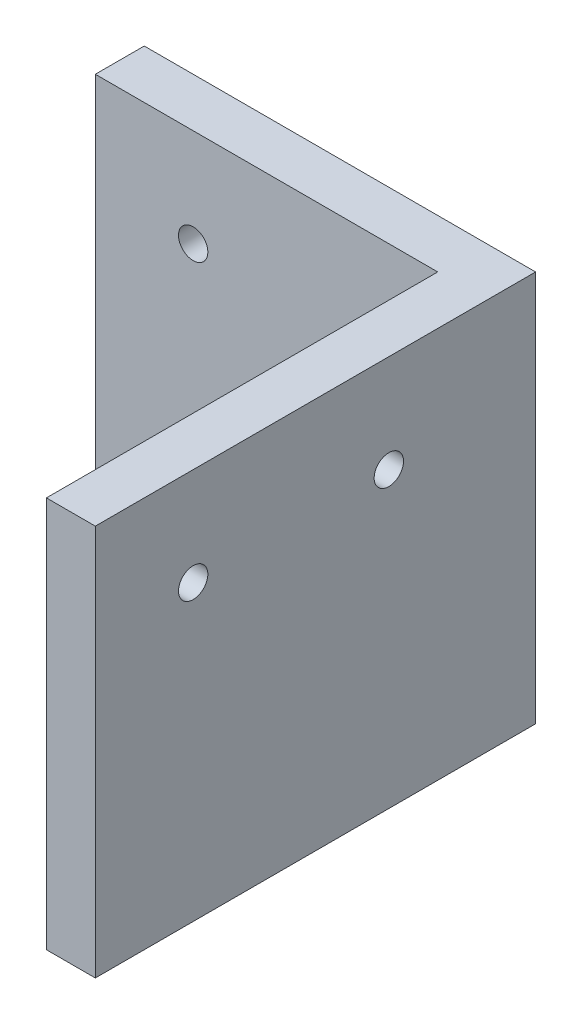
SolidWorks part; units mm, degrees
ref_plane "Front Plane" through (0, 0, 0) normal (0, 0, 1) x (1, 0, 0)
ref_plane "Top Plane" through (0, 0, 0) normal (0, 1, 0) x (1, 0, 0)
ref_plane "Right Plane" through (0, 0, 0) normal (1, 0, 0) x (0, 0, -1)
sketch "Sketch1" plane through (0, 0, 0) normal (0, 0, 1) x (1, 0, 0)
  line L0 (0, 0) -> (0, 95)
  line L1 (0, 95) -> (20, 95)
  line L2 (20, 95) -> (20, 75)
  line L3 (20, 75) -> (40, 75)
  line L4 (40, 75) -> (40, 80)
  line L5 (40, 80) -> (50, 80)
  line L6 (50, 80) -> (50, 75)
  line L7 (50, 75) -> (70, 75)
  line L8 (70, 75) -> (70, 80)
  line L9 (70, 80) -> (80, 80)
  line L10 (80, 80) -> (80, 15)
  line L11 (80, 15) -> (445, 15)
  line L23 (237.9167, 0) -> (0, 0)
  line L24 (262.5, 146.857) -> (262.5, -30.5268)
  line L25 (287.0833, 0) -> (525, 0)
  line L26 (445, 80) -> (445, 15)
  line L27 (455, 80) -> (445, 80)
  line L28 (455, 75) -> (455, 80)
  line L29 (475, 75) -> (455, 75)
  line L30 (485, 80) -> (475, 80)
  line L31 (485, 75) -> (485, 80)
  line L32 (505, 75) -> (485, 75)
  line L33 (505, 95) -> (505, 75)
  line L34 (525, 95) -> (505, 95)
  line L35 (525, 0) -> (525, 95)
  line L36 (475, 75) -> (475, 80)
  line L37 (237.9167, 0) -> (287.0833, 0)
  point P19 (262.5, 15)
  dimension "D1" = 10
  dimension "D2" = 10
  dimension "D3" = 182.5
  dimension "D4" = 20
  dimension "D5" = 20
  dimension "D6" = 20
  dimension "D7" = 20
  dimension "D8" = 5
  dimension "D9" = 5
  dimension "D10" = 65
  dimension "D11" = 80
  dimension "D12" = 95
extrude "Boss-Extrude1" add sketch "Sketch1" along normal blind 597.1 contours L23 L37 L24 L11 L10 L9 L8 L7 L6 L5 L4 L3 L2 L1 L0 | L24 L37 L25 L35 L34 L33 L32 L31 L30 L36 L29 L28 L27 L26 L11
sketch "Sketch2" plane through (0, 15, 0) normal (0, 1, 0) x (1, 0, 0)
  line L0 (80, 0) -> (445, 0) construction
  line L1 (187.3, 0) -> (252.5, 0)
  line L2 (187.3, 0) -> (187.3, -400)
  line L3 (187.3, -400) -> (252.5, -400)
  line L4 (252.5, 0) -> (252.5, -400)
  line L5 (80, -597.1) -> (445, -597.1) construction
  line L6 (272.5, -597.1) -> (337.7, -597.1)
  line L7 (272.5, -597.1) -> (272.5, -197.1)
  line L8 (272.5, -197.1) -> (337.7, -197.1)
  line L9 (337.7, -597.1) -> (337.7, -197.1)
  line L10 (445, -597.1) -> (445, 0) construction
  dimension "D1" = 400
  dimension "D2" = 400
  dimension "D3" = 65.2
  dimension "D4" = 65.2
  dimension "D5" = 20
  dimension "D6" = 107.3
extrude "Cut-Extrude1" cut sketch "Sketch2" against normal through all
sketch "Sketch3" plane through (0, 15, 0) normal (0, 1, 0) x (1, 0, 0)
  line L1 (80, 0) -> (445, 0)
  line L2 (80, 0) -> (80, -597.1)
  line L3 (80, -597.1) -> (445, -597.1)
  line L4 (445, 0) -> (445, -597.1)
  line L5 (187.3, 0) -> (252.5, 0)
  line L6 (187.3, 0) -> (187.3, -400)
  line L7 (187.3, -400) -> (252.5, -400)
  line L8 (252.5, 0) -> (252.5, -400)
  line L9 (272.5, -197.1) -> (337.7, -197.1)
  line L10 (272.5, -197.1) -> (272.5, -597.1)
  line L11 (272.5, -597.1) -> (337.7, -597.1)
  line L12 (337.7, -197.1) -> (337.7, -597.1)
  line M1 (187.3, -400) -> (187.3, 0)
  line M2 (187.3, 0) -> (80, 0)
  line M3 (80, 0) -> (80, -597.1)
  line M4 (80, -597.1) -> (272.5, -597.1)
  line M5 (272.5, -597.1) -> (272.5, -197.1)
  line M6 (272.5, -197.1) -> (337.7, -197.1)
  line M7 (337.7, -197.1) -> (337.7, -597.1)
  line M8 (337.7, -597.1) -> (445, -597.1)
  line M9 (445, -597.1) -> (445, 0)
  line M10 (445, 0) -> (252.5, 0)
  line M11 (252.5, 0) -> (252.5, -400)
  line M12 (252.5, -400) -> (187.3, -400)
extrude "Boss-Extrude2" add sketch "Sketch3" along normal blind 8 contours M12 M1 M2 M3 M4 M5 M6 M7 M8 M9 M10 M11
sketch "Sketch4" plane through (0, 0, 0) normal (0, -1, 0) x (1, 0, 0)
  line L1 (0, 597.1) -> (525, 597.1)
  line L2 (0, 597.1) -> (0, 0)
  line L3 (0, 0) -> (525, 0)
  line L4 (525, 597.1) -> (525, 0)
extrude "Boss-Extrude3" add sketch "Sketch4" along normal blind 7
sketch "Sketch5" plane through (0, 23, 0) normal (0, 1, 0) x (1, 0, 0)
  line L1 (80, 0) -> (445, 0)
  line L2 (80, 0) -> (80, -597.1)
  line L3 (80, -597.1) -> (445, -597.1)
  line L4 (445, 0) -> (445, -597.1)
extrude "Cut-Extrude2" cut sketch "Sketch5" against normal blind 10
sketch "Sketch6" plane through (525, 0, 0) normal (1, 0, 0) x (0, 0, -1)
  line L0 (-597.1, 95) -> (0, 95) construction
  line L1 (-324.55, 95) -> (-272.55, 95)
  line L2 (-324.55, 95) -> (-324.55, 55)
  line L3 (-324.55, 55) -> (-272.55, 55)
  line L4 (-272.55, 95) -> (-272.55, 55)
  line L6 (-597.1, -7) -> (-597.1, 95) construction
  circle A0 centre (-318.55, 79) radius 2.125
  circle A1 centre (-278.55, 79) radius 2.125
  circle A2 centre (-278.55, 63) radius 2.125
  circle A3 centre (-318.55, 63) radius 2.125
  circle A4 centre (-318.55, 79) radius 2.125
  circle A5 centre (-278.55, 79) radius 2.125
  circle A6 centre (-278.55, 63) radius 2.125
  circle A7 centre (-318.55, 63) radius 2.125
  dimension "D4" = 4.25
  dimension "D1" = 52
  dimension "D2" = 40
  dimension "D3" = 272.55
  dimension "D5" = 40
  dimension "D6" = 40
  dimension "D7" = 16
  dimension "D8" = 16
  dimension "D9" = 6
  dimension "D10" = 8
extrude "Cut-Extrude3" cut sketch "Sketch6" against normal up to next contours A0 | A3 | A2 | A1
cosmetic thread "Cosmetic Thread5" parameters "D2"=5.5
cosmetic thread "Cosmetic Thread6" parameters "D2"=5.5
cosmetic thread "Cosmetic Thread7" parameters "D2"=5.5
cosmetic thread "Cosmetic Thread8" parameters "D2"=5.5
sketch "Sketch7" plane through (0, 75, 0) normal (0, 1, 0) x (1, 0, 0)
  line L1 (485, 0) -> (505, 0)
  line L2 (485, 0) -> (485, -597.1)
  line L3 (485, -597.1) -> (505, -597.1)
  line L4 (505, 0) -> (505, -597.1)
extrude "Cut-Extrude4" cut sketch "Sketch7" against normal blind 5
sketch "Sketch8" plane through (445, 0, 0) normal (-1, 0, 0) x (0, 0, 1)
  line L0 (597.1, 80) -> (0, 80) construction
  line L1 (269.8676, 50) -> (324.923, 50)
  line L2 (269.8676, 50) -> (269.8676, 70)
  line L3 (269.8676, 70) -> (324.923, 70)
  line L4 (324.923, 50) -> (324.923, 70)
  dimension "D1" = 20
  dimension "D2" = 55.0555
  dimension "D3" = 10
extrude "Cut-Extrude6" cut sketch "Sketch8" against normal blind 60
sketch "Sketch13" plane through (0, 50, 0) normal (0, 1, 0) x (1, 0, 0)
  line L0 (445, -269.8676) -> (445, -324.923) construction
  line L1 (445, -290.3007) -> (485, -290.3007)
  line L2 (445, -290.3007) -> (445, -305.3007)
  line L3 (445, -305.3007) -> (485, -305.3007)
  line L4 (485, -290.3007) -> (485, -305.3007)
  dimension "D1" = 15
  dimension "D2" = 40
extrude "Boss-Extrude4" add sketch "Sketch13" along normal up to next
sketch "Sketch14" plane through (0, 75, 0) normal (0, 1, 0) x (1, 0, 0)
  line L1 (20, 0) -> (40, 0)
  line L2 (20, 0) -> (20, -597.1)
  line L3 (20, -597.1) -> (40, -597.1)
  line L4 (40, 0) -> (40, -597.1)
extrude "Cut-Extrude7" cut sketch "Sketch14" against normal blind 5
sketch "Sketch15" plane through (0, 0, 0) normal (-1, 0, 0) x (0, 0, 1)
  line L0 (597.1, 95) -> (0, 95) construction
  line L1 (10, 95) -> (37, 95)
  line L2 (10, 95) -> (10, 49.6)
  line L3 (10, 49.6) -> (37, 49.6)
  line L4 (37, 95) -> (37, 49.6)
  line L5 (0, -7) -> (0, 95) construction
  line L10 (298.55, -7) -> (298.55, 95)
  line L11 (597.1, -7) -> (0, -7) construction
  line L12 (587.1, 49.6) -> (560.1, 49.6)
  line L13 (587.1, 95) -> (560.1, 95)
  line L14 (587.1, 95) -> (587.1, 49.6)
  line L15 (560.1, 95) -> (560.1, 49.6)
  circle A0 centre (13.5, 82.3) radius 1.33
  circle A1 centre (33.5, 82.3) radius 1.33
  circle A2 centre (33.5, 62.3) radius 1.33
  circle A3 centre (13.5, 62.3) radius 1.33
  circle A4 centre (563.6, 62.3) radius 1.33
  circle A5 centre (563.6, 82.3) radius 1.33
  circle A6 centre (583.6, 82.3) radius 1.33
  circle A7 centre (583.6, 62.3) radius 1.33
  circle A8 centre (13.5, 82.3) radius 1.33
  circle A9 centre (33.5, 82.3) radius 1.33
  circle A10 centre (33.5, 62.3) radius 1.33
  circle A11 centre (13.5, 62.3) radius 1.33
  dimension "D2" = 2.66
  dimension "D1" = 10
  dimension "D3" = 45.4
  dimension "D4" = 27
  dimension "D5" = 20
  dimension "D6" = 20
  dimension "D7" = 20
  dimension "D8" = 20
  dimension "D9" = 3.5
  dimension "D10" = 12.7
extrude "Cut-Extrude8" cut sketch "Sketch15" against normal up to next contours A0 | A1 | A3 | A2 | A5 | A7 | A4 | A6
cosmetic thread "Cosmetic Thread9" parameters "D2"=3.2
cosmetic thread "Cosmetic Thread10" parameters "D2"=3.2
cosmetic thread "Cosmetic Thread11" parameters "D2"=3.2
cosmetic thread "Cosmetic Thread12" parameters "D2"=3.2
cosmetic thread "Cosmetic Thread13" parameters "D2"=3.2
cosmetic thread "Cosmetic Thread14" parameters "D2"=3.2
cosmetic thread "Cosmetic Thread15" parameters "D2"=3.2
cosmetic thread "Cosmetic Thread16" parameters "D2"=3.2
sketch "Sketch16" plane through (80, 0, 0) normal (1, 0, 0) x (0, 0, -1)
  line L0 (-597.1, 80) -> (-597.1, 13) construction
  line L1 (-592.1, 70) -> (-557.1, 70)
  line L2 (-592.1, 70) -> (-592.1, 55)
  line L3 (-592.1, 55) -> (-557.1, 55)
  line L4 (-557.1, 70) -> (-557.1, 55)
  line L5 (-597.1, 80) -> (0, 80) construction
  line L6 (0, 80) -> (0, 13) construction
  line L7 (-40, 55) -> (-5, 55)
  line L8 (-40, 55) -> (-40, 70)
  line L9 (-40, 70) -> (-5, 70)
  line L10 (-5, 55) -> (-5, 70)
  dimension "D1" = 5
  dimension "D2" = 15
  dimension "D3" = 10
  dimension "D4" = 35
  dimension "D5" = 10
  dimension "D6" = 5
  dimension "D7" = 35
  dimension "D8" = 15
extrude "Cut-Extrude9" cut sketch "Sketch16" against normal blind 60
sketch "Sketch17" plane through (0, -7, 0) normal (0, -1, 0) x (1, 0, 0)
  line L0 (525, 0) -> (525, 597.1) construction
  line L1 (465, 373.55) -> (525, 373.55)
  line L2 (465, 373.55) -> (465, 223.55)
  line L3 (465, 223.55) -> (525, 223.55)
  line L4 (525, 373.55) -> (525, 223.55)
  line L5 (525, 597.1) -> (0, 597.1) construction
  dimension "D1" = 150
  dimension "D2" = 223.55
  dimension "D3" = 60
extrude "Cut-Extrude10" cut sketch "Sketch17" against normal blind 40
sketch "Sketch18" plane through (0, 13, 0) normal (0, 1, 0) x (1, 0, 0)
  line L1 (427, -286.05) -> (415, -286.05)
  line L2 (427, -286.05) -> (427, -302.05)
  line L3 (427, -302.05) -> (415, -302.05)
  line L4 (415, -286.05) -> (415, -302.05)
  line L5 (417, -286.05) -> (425, -286.05)
  line L6 (445, 0) -> (252.5, 0) construction
  line L7 (417, -286.05) -> (417, -279.05)
  line L8 (445, -597.1) -> (445, 0) construction
  line L9 (417, -279.05) -> (425, -279.05)
  line L10 (425, -286.05) -> (425, -279.05)
  line L11 (417, -302.05) -> (425, -302.05)
  line L12 (417, -302.05) -> (417, -309.05)
  line L13 (417, -309.05) -> (425, -309.05)
  line L14 (425, -302.05) -> (425, -309.05)
  dimension "D1" = 12
  dimension "D2" = 16
  dimension "D3" = 286.05
  dimension "D4" = 30
  dimension "D5" = 8
  dimension "D6" = 7
  dimension "D7" = 2
  dimension "D8" = 8
  dimension "D9" = 7
  dimension "D10" = 2
extrude "Cut-Extrude11" cut sketch "Sketch18" against normal through all contours L1 L4 L3 L2
sketch "Sketch19" plane through (0, 13, 0) normal (0, 1, 0) x (1, 0, 0)
  line L0 (427, -286.05) -> (415, -286.05) construction
  line L1 (417, -286.05) -> (425, -286.05)
  line L2 (417, -286.05) -> (417, -279.05)
  line L3 (417, -279.05) -> (425, -279.05)
  line L4 (425, -286.05) -> (425, -279.05)
  line L5 (427, -302.05) -> (415, -302.05) construction
  line L6 (417, -302.05) -> (425, -302.05)
  line L7 (417, -302.05) -> (417, -309.05)
  line L8 (417, -309.05) -> (425, -309.05)
  line L9 (425, -302.05) -> (425, -309.05)
  line L10 (415, -286.05) -> (415, -302.05) construction
  dimension "D1" = 8
  dimension "D2" = 8
  dimension "D3" = 7
  dimension "D4" = 7
  dimension "D5" = 2
  dimension "D6" = 2
extrude "Cut-Extrude12" cut sketch "Sketch19" against normal blind 10
sketch "Sketch20" plane through (525, 0, 0) normal (1, 0, 0) x (0, 0, -1)
  circle A0 centre (-318.55, 79) radius 2.7599
  circle A1 centre (-318.55, 63) radius 2.758
  circle A2 centre (-278.55, 63) radius 2.7761
  circle A3 centre (-278.55, 79) radius 2.7514
extrude "Cut-Extrude13" cut sketch "Sketch20" against normal up to next
sketch "Sketch21" plane through (0, 0, 0) normal (-1, 0, 0) x (0, 0, 1)
  circle A0 centre (13.5, 82.3) radius 1.6434
  circle A1 centre (13.5, 62.3) radius 1.6389
  circle A2 centre (33.5, 62.3) radius 1.6445
  circle A3 centre (33.5, 82.3) radius 1.706
  circle A4 centre (563.6, 62.3) radius 1.6454
  circle A5 centre (583.6, 62.3) radius 1.6466
  circle A6 centre (583.6, 82.3) radius 1.6613
  circle A7 centre (563.6, 82.3) radius 1.7012
extrude "Cut-Extrude14" cut sketch "Sketch21" against normal up to next
sketch "Sketch22" plane through (445, 0, 0) normal (-1, 0, 0) x (0, 0, 1)
  line L1 (290.3007, 70) -> (305.3007, 70)
  line L2 (290.3007, 70) -> (290.3007, 50)
  line L3 (290.3007, 50) -> (305.3007, 50)
  line L4 (305.3007, 70) -> (305.3007, 50)
extrude "Cut-Extrude15" cut sketch "Sketch22" against normal up to next
sketch "Sketch24" plane through (525, 0, 0) normal (1, 0, 0) x (0, 0, -1)
  line L0 (-597.1, -7) -> (-597.1, 95) construction
  line L1 (-597.1, 95) -> (0, 95) construction
  line L4 (0, -7) -> (0, 95) construction
  circle A0 centre (-583.6, 82.3) radius 1.5
  circle A1 centre (-563.6, 82.3) radius 1.5
  circle A2 centre (-583.6, 62.3) radius 1.5
  circle A3 centre (-563.6, 62.3) radius 1.5
  circle A4 centre (-33.5, 82.3) radius 1.5
  circle A5 centre (-13.5, 82.3) radius 1.5
  circle A6 centre (-13.5, 62.3) radius 1.5
  circle A7 centre (-33.5, 62.3) radius 1.5
  dimension "D1" = 3
  dimension "D2" = 13.5
  dimension "D3" = 12.7
  dimension "D4" = 20
  dimension "D5" = 13.5
  dimension "D6" = 12.7
  dimension "D7" = 20
  dimension "D8" = 20
  dimension "D9" = 20
  dimension "D10" = 13.5
  dimension "D11" = 20
  dimension "D12" = 20
  dimension "D13" = 20
  dimension "D14" = 20
  dimension "D15" = 12.7
  dimension "D16" = 13.5
  dimension "D17" = 12.7
extrude "Cut-Extrude16" cut sketch "Sketch24" against normal up to next
sketch "Sketch27" plane through (445, 0, 0) normal (-1, 0, 0) x (0, 0, 1)
  line L0 (597.1, 80) -> (0, 80) construction
  line L1 (592.1, 70) -> (557.1, 70)
  line L2 (592.1, 70) -> (592.1, 55)
  line L3 (592.1, 55) -> (557.1, 55)
  line L4 (557.1, 70) -> (557.1, 55)
  line L5 (597.1, 80) -> (597.1, 13) construction
  dimension "D1" = 10
  dimension "D2" = 5
  dimension "D3" = 35
  dimension "D4" = 15
extrude "Cut-Extrude17" cut sketch "Sketch27" against normal blind 60
sketch "Sketch28" plane through (445, 0, 0) normal (-1, 0, 0) x (0, 0, 1)
  line L1 (0, 80) -> (40, 80)
  line L2 (0, 80) -> (0, 55)
  line L3 (0, 55) -> (40, 55)
  line L4 (40, 80) -> (40, 55)
  line L5 (40, 55) -> (5, 55)
  line L6 (40, 55) -> (40, 70)
  line L7 (40, 70) -> (5, 70)
  line L8 (5, 55) -> (5, 70)
  circle M9 centre (13.5, 62.3) radius 1.5
  circle M10 centre (33.5, 62.3) radius 1.5
  dimension "D1" = 40
  dimension "D2" = 25
  dimension "D3" = 15
  dimension "D4" = 35
extrude "Cut-Extrude18" cut sketch "Sketch28" against normal blind 60 contours L8 L3 L4 L7 M10 M9
sketch "Sketch29" plane through (0, -7, 0) normal (0, -1, 0) x (1, 0, 0)
  line L0 (0, 597.1) -> (0, 0) construction
  line L1 (0, 373.55) -> (60, 373.55)
  line L2 (0, 373.55) -> (0, 223.55)
  line L3 (0, 223.55) -> (60, 223.55)
  line L4 (60, 373.55) -> (60, 223.55)
  dimension "D1" = 60
  dimension "D2" = 150
extrude "Cut-Extrude19" cut sketch "Sketch29" against normal blind 40
sketch "Sketch33" plane through (0, 0, 0) normal (-1, 0, 0) x (0, 0, 1)
  line L0 (597.1, 95) -> (0, 95) construction
  line L1 (597.1, -7) -> (597.1, 95) construction
  circle A0 centre (318.55, 79) radius 2.5
  circle A1 centre (319.3565, 63) radius 2.5
  circle A2 centre (278.55, 79) radius 2.5
  circle A3 centre (279.3565, 63) radius 2.5
  dimension "D1" = 5
  dimension "D2" = 40
  dimension "D3" = 16
  dimension "D4" = 40
  dimension "D5" = 16
  dimension "D6" = 16
  dimension "D7" = 278.55
extrude "Cut-Extrude20" cut sketch "Sketch33" against normal up to next
sketch "Sketch37" plane through (80, 0, 0) normal (1, 0, 0) x (0, 0, -1)
  line L0 (-597.1, 80) -> (0, 80) construction
  line L1 (-327.18, 50) -> (-272.18, 50)
  line L2 (-327.18, 50) -> (-327.18, 70)
  line L3 (-327.18, 70) -> (-272.18, 70)
  line L4 (-272.18, 50) -> (-272.18, 70)
  line L5 (0, 80) -> (0, 13) construction
  dimension "D1" = 20
  dimension "D2" = 55
  dimension "D3" = 10
  dimension "D4" = 272.18
extrude "Cut-Extrude21" cut sketch "Sketch37" against normal blind 60
sketch "Sketch39" plane through (0, 0, 0) normal (-1, 0, 0) x (0, 0, 1)
  line L0 (597.1, 95) -> (0, 95) construction
  line L1 (3, 95) -> (8, 95)
  line L2 (3, 95) -> (3, 55)
  line L3 (3, 55) -> (8, 55)
  line L4 (8, 95) -> (8, 55)
  line L5 (0, -7) -> (0, 95) construction
  line L6 (597.1, -7) -> (597.1, 95) construction
  line L7 (589.1, 95) -> (594.1, 95)
  line L8 (589.1, 95) -> (589.1, 55)
  line L9 (589.1, 55) -> (594.1, 55)
  line L10 (594.1, 95) -> (594.1, 55)
  dimension "D1" = 3
  dimension "D2" = 5
  dimension "D3" = 40
  dimension "D4" = 3
  dimension "D5" = 5
  dimension "D6" = 40
extrude "Boss-Extrude6" add sketch "Sketch39" along normal blind 40
sketch "Sketch41" plane through (0, 0, 3) normal (0, 0, -1) x (-1, 0, 0)
  line L0 (40, 95) -> (0, 95) construction
  line L1 (40, 95) -> (40, 55) construction
  circle A0 centre (10, 85) radius 1.5
  circle A1 centre (30, 85) radius 1.5
  circle A2 centre (30, 65) radius 1.5
  circle A3 centre (10, 65) radius 1.5
  dimension "D1" = 3
  dimension "D2" = 20
  dimension "D3" = 20
  dimension "D4" = 20
  dimension "D5" = 20
  dimension "D6" = 10
  dimension "D7" = 10
  dimension "D8" = 10
extrude "Cut-Extrude22" cut sketch "Sketch41" against normal through all
sketch "Sketch42" plane through (80, 0, 0) normal (1, 0, 0) x (0, 0, -1)
  line L1 (-592.1, 70) -> (-557.1, 70)
  line L2 (-592.1, 70) -> (-592.1, 55)
  line L3 (-592.1, 55) -> (-557.1, 55)
  line L4 (-557.1, 70) -> (-557.1, 55)
  line L5 (-40, 70) -> (-5, 70)
  line L6 (-40, 70) -> (-40, 55)
  line L7 (-40, 55) -> (-5, 55)
  line L8 (-5, 70) -> (-5, 55)
extrude "Boss-Extrude7" add sketch "Sketch42" against normal blind 60
sketch "Sketch43" plane through (0, 0, 0) normal (-1, 0, 0) x (0, 0, 1)
  line L0 (589.1, 95) -> (8, 95) construction
  line L1 (8, 95) -> (49.1479, 95)
  line L2 (8, 95) -> (8, 53.381)
  line L3 (8, 53.381) -> (49.1479, 53.381)
  line L4 (49.1479, 95) -> (49.1479, 53.381)
  line L5 (546.6637, 95) -> (589.1, 95)
  line L6 (546.6637, 95) -> (546.6637, 55)
  line L7 (546.6637, 55) -> (589.1, 55)
  line L8 (589.1, 95) -> (589.1, 55)
extrude "Boss-Extrude8" add sketch "Sketch43" against normal blind 20
sketch "Sketch44" plane through (525, 0, 0) normal (1, 0, 0) x (0, 0, -1)
  line L0 (-597.1, 95) -> (0, 95) construction
  line L1 (-597.1, 95) -> (-547.4631, 95)
  line L2 (-597.1, 95) -> (-597.1, 48.775)
  line L3 (-597.1, 48.775) -> (-547.4631, 48.775)
  line L4 (-547.4631, 95) -> (-547.4631, 48.775)
  line L5 (-1.3119, 95) -> (-48.1855, 95)
  line L6 (-1.3119, 95) -> (-1.3119, 48.775)
  line L7 (-1.3119, 48.775) -> (-48.1855, 48.775)
  line L8 (-48.1855, 95) -> (-48.1855, 48.775)
extrude "Boss-Extrude9" add sketch "Sketch44" against normal blind 20
sketch "Sketch45" plane through (445, 0, 0) normal (-1, 0, 0) x (0, 0, 1)
  line L1 (5, 70) -> (40, 70)
  line L2 (5, 70) -> (5, 55)
  line L3 (5, 55) -> (40, 55)
  line L4 (40, 70) -> (40, 55)
  line L5 (557.1, 70) -> (592.1, 70)
  line L6 (557.1, 70) -> (557.1, 55)
  line L7 (557.1, 55) -> (592.1, 55)
  line L8 (592.1, 70) -> (592.1, 55)
extrude "Boss-Extrude10" add sketch "Sketch45" against normal blind 60
sketch "Sketch46" plane through (525, 0, 0) normal (1, 0, 0) x (0, 0, -1)
  line L0 (-597.1, 95) -> (0, 95) construction
  line L1 (-594.1, 95) -> (-589.1, 95)
  line L2 (-594.1, 95) -> (-594.1, 55)
  line L3 (-594.1, 55) -> (-589.1, 55)
  line L4 (-589.1, 95) -> (-589.1, 55)
  line L5 (-597.1, -7) -> (-597.1, 95) construction
  line L6 (0, -7) -> (0, 95) construction
  line L7 (-8, 95) -> (-3, 95)
  line L8 (-8, 95) -> (-8, 55)
  line L9 (-8, 55) -> (-3, 55)
  line L10 (-3, 95) -> (-3, 55)
  dimension "D1" = 5
  dimension "D2" = 40
  dimension "D3" = 3
  dimension "D4" = 5
  dimension "D5" = 3
  dimension "D6" = 40
extrude "Boss-Extrude11" add sketch "Sketch46" along normal blind 40
sketch "Sketch47" plane through (0, 0, 3) normal (0, 0, -1) x (-1, 0, 0)
  line L0 (-565, 95) -> (-525, 95) construction
  line L1 (-565, 55) -> (-565, 95) construction
  circle A0 centre (-555, 85) radius 1.5
  circle A1 centre (-535, 84.6583) radius 1.5
  circle A2 centre (-535, 64.6583) radius 1.5
  circle A3 centre (-555, 65) radius 1.5
  dimension "D7" = 3
  dimension "D1" = 10
  dimension "D2" = 10
  dimension "D3" = 20
  dimension "D4" = 20
  dimension "D5" = 20
  dimension "D6" = 20
  dimension "D8" = 10
extrude "Cut-Extrude23" cut sketch "Sketch47" against normal through all
fillet "Fillet1" radius 5 1 edges at (0, 75, 8)
fillet "Fillet2" radius 5 3 edges at (525, 75, 8) (525, 75, 589.1) (0, 75, 589.1)
sketch "Sketch51" plane through (0, 0, 0) normal (-1, 0, 0) x (0, 0, 1)
  line L0 (584.1, 95) -> (13, 95) construction
  line L1 (48, 95) -> (8, 95)
  line L2 (48, 95) -> (48, 55)
  line L3 (48, 55) -> (8, 55)
  line L4 (8, 95) -> (8, 55)
  line L5 (8, 55) -> (8, 95) construction
  line L6 (8, 55) -> (8, 95) construction
  dimension "D1" = 40
extrude "Boss-Extrude12" add sketch "Sketch51" along normal blind 5
sketch "Sketch52" plane through (-5, 0, 0) normal (-1, 0, 0) x (0, 0, 1)
  line L0 (8, 55) -> (8, 95) construction
  line L1 (48, 95) -> (8, 95) construction
  circle A0 centre (18, 85) radius 3
  circle A1 centre (28, 85) radius 3
  circle A2 centre (38, 85) radius 3
  dimension "D1" = 6
  dimension "D2" = 10
  dimension "D3" = 10
  dimension "D4" = 10
  dimension "D5" = 10
extrude "Cut-Extrude26" cut sketch "Sketch52" against normal through all
sketch "Sketch53" plane through (-5, 0, 0) normal (-1, 0, 0) x (0, 0, 1)
  circle A0 centre (28, 85) radius 3.2804
extrude "Boss-Extrude13" add sketch "Sketch53" against normal through all
sketch "Sketch54" plane through (565, 0, 0) normal (1, 0, 0) x (0, 0, -1)
  circle A0 centre (-28, 85) radius 3.2804
extrude "Cut-Extrude27" cut sketch "Sketch54" against normal blind 40
sketch "Sketch55" plane through (0, 0, 0) normal (0, 0, -1) x (-1, 0, 0)
  line L0 (-20, 95) -> (-20, 70) construction
  line L1 (-505, 95) -> (-20, 95)
  line L2 (-505, 95) -> (-505, 80.5212)
  line L3 (-505, 80.5212) -> (-20, 80.5212)
  line L4 (-20, 95) -> (-20, 80.5212)
extrude "Cut-Extrude28" cut sketch "Sketch55" against normal blind 40
sketch "Sketch57" plane through (0, 0, 0) normal (0, 0, -1) x (-1, 0, 0)
  line L1 (0, 95) -> (-723.1869, 95)
  line L2 (0, 95) -> (0, -65.7079)
  line L3 (0, -65.7079) -> (-723.1869, -65.7079)
  line L4 (-723.1869, 95) -> (-723.1869, -65.7079)
extrude "Cut-Extrude30" cut sketch "Sketch57" against normal through all
sketch "Sketch58" plane through (-5, 0, 0) normal (-1, 0, 0) x (0, 0, 1)
  circle A0 centre (18, 85) radius 1.5
  circle A1 centre (38, 85) radius 1.5
  circle A2 centre (18, 85) radius 4.6957
  circle A3 centre (38, 85) radius 4.8629
  dimension "D1" = 3
  dimension "D2" = 3
extrude "Boss-Extrude14" add sketch "Sketch58" against normal blind 5
sketch "Sketch59" plane through (-5, 0, 0) normal (-1, 0, 0) x (0, 0, 1)
  circle A0 centre (18, 85) radius 3.5
  circle A1 centre (38, 85) radius 3.5
  dimension "D1" = 7
  dimension "D2" = 7
extrude "Cut-Extrude31" cut sketch "Sketch59" against normal blind 1.5
